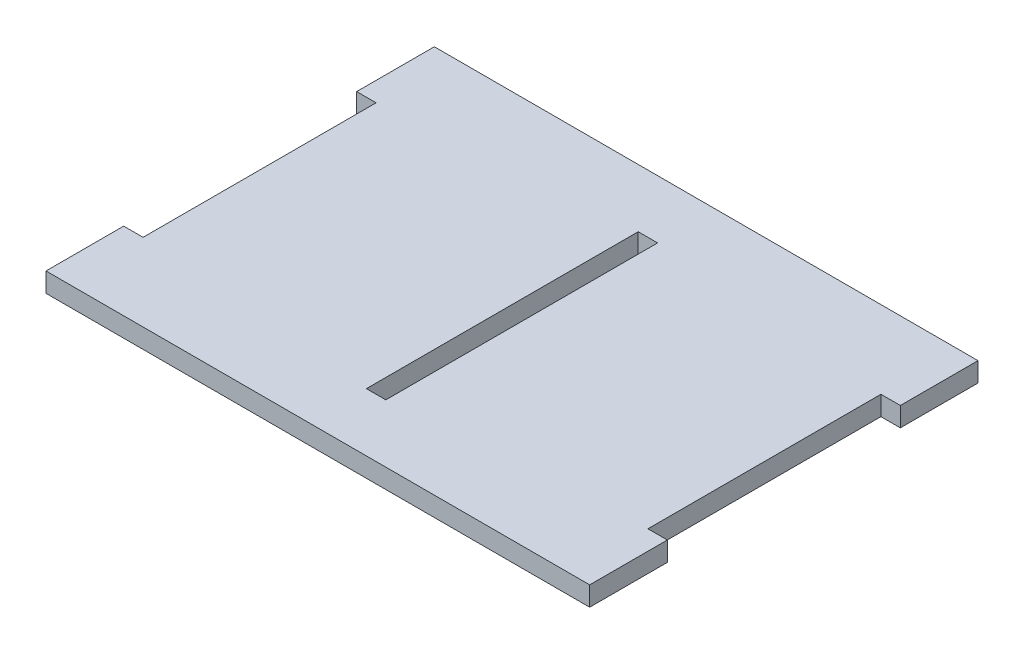
SolidWorks part; units mm, degrees
material "Balsa"
ref_plane "Front Plane" through (0, 0, 0) normal (0, 0, 1) x (1, 0, 0)
ref_plane "Top Plane" through (0, 0, 0) normal (0, 1, 0) x (1, 0, 0)
ref_plane "Right Plane" through (0, 0, 0) normal (1, 0, 0) x (0, 0, -1)
sketch "Sketch1" plane through (0, 0, 0) normal (0, 1, 0) x (1, 0, 0)
  line L0 (-41.275, -19.05) -> (-41.275, 19.05)
  line L1 (-41.275, -31.75) -> (41.275, -31.75)
  line L2 (-41.275, 31.75) -> (41.275, 31.75)
  line L3 (41.275, -19.05) -> (41.275, 19.05)
  line L4 (-41.275, -31.75) -> (41.275, 31.75) construction
  line L5 (-41.275, 31.75) -> (41.275, -31.75) construction
  line L6 (41.275, 31.75) -> (44.45, 31.75)
  line L7 (44.45, 31.75) -> (44.45, 19.05)
  line L8 (44.45, 19.05) -> (41.275, 19.05)
  line L9 (-1.2611, 0) -> (1.2611, 0) construction
  line L10 (0, 31.75) -> (0, -31.75) construction
  line L11 (44.45, -19.05) -> (41.275, -19.05)
  line L12 (44.45, -31.75) -> (44.45, -19.05)
  line L13 (41.275, -31.75) -> (44.45, -31.75)
  line L14 (-41.275, 31.75) -> (-44.45, 31.75)
  line L15 (-44.45, 31.75) -> (-44.45, 19.05)
  line L16 (-44.45, 19.05) -> (-41.275, 19.05)
  line L17 (-44.45, -19.05) -> (-41.275, -19.05)
  line L18 (-41.275, -31.75) -> (-44.45, -31.75)
  line L19 (-44.45, -31.75) -> (-44.45, -19.05)
  point P1 (0, 0)
  point P13 (42.8625, 19.05)
  point P14 (42.8625, -19.05)
  dimension "D1" = 38.1
  dimension "D2" = 12.7
  dimension "D3" = 3.175
  dimension "D4" = 88.9
extrude "Boss-Extrude1" add sketch "Sketch1" along normal blind 3.175
sketch "Sketch2" plane through (0, 3.175, 0) normal (0, 1, 0) x (1, 0, 0)
  line L0 (44.45, 31.75) -> (-44.45, 31.75) construction
  line L1 (-1.5875, 22.225) -> (1.5875, 22.225)
  line L2 (-1.5875, 22.225) -> (-1.5875, -22.225)
  line L3 (-1.5875, -22.225) -> (1.5875, -22.225)
  line L4 (1.5875, 22.225) -> (1.5875, -22.225)
  line L7 (-44.45, -19.05) -> (-44.45, -31.75) construction
  point P4 (0, 22.225)
  dimension "D1" = 44.45
  dimension "D2" = 9.525
  dimension "D3" = 3.175
  dimension "D4" = 42.8625
extrude "Cut-Extrude1" cut sketch "Sketch2" against normal blind 3.175
